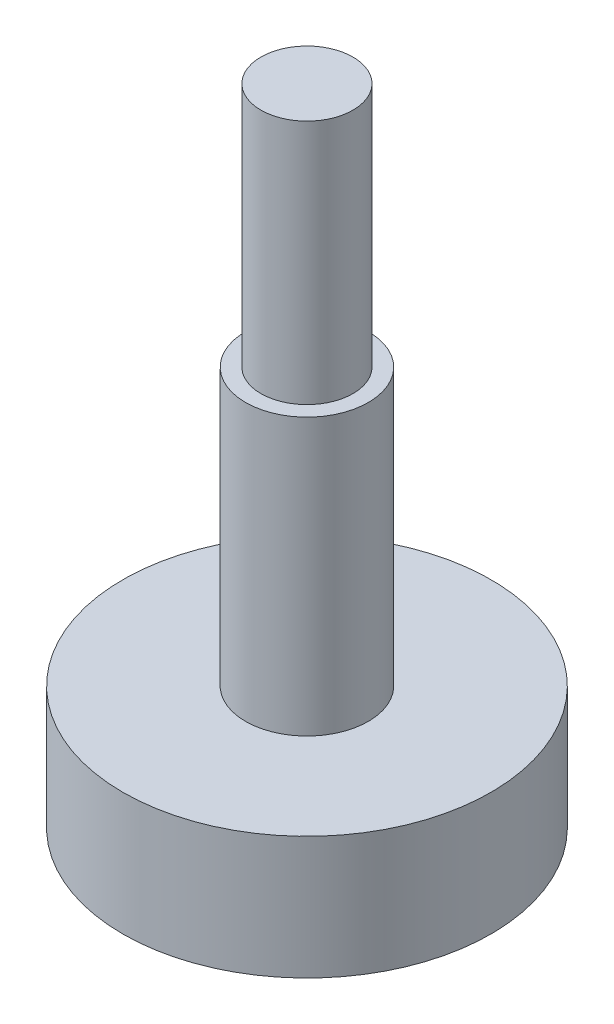
SolidWorks part; units mm, degrees
ref_plane "Front Plane" through (0, 0, 0) normal (0, 0, 1) x (1, 0, 0)
ref_plane "Top Plane" through (0, 0, 0) normal (0, 1, 0) x (1, 0, 0)
ref_plane "Right Plane" through (0, 0, 0) normal (1, 0, 0) x (0, 0, -1)
sketch "Sketch1" plane through (0, 0, 0) normal (0, 0, 1) x (1, 0, 0)
  line L0 (0, 0) -> (6, 0)
  line L1 (5.5, 0) -> (-5.5, 0) construction
  line L2 (6, 0) -> (6, 4)
  line L3 (6, 4) -> (2, 4)
  line L4 (2, 4) -> (2, 13)
  line L5 (2, 13) -> (1.5, 13)
  line L6 (0, -5.5) -> (0, 5.5) construction
  line L7 (0, 21) -> (0, 0)
  line L8 (1.5, 13) -> (1.5, 21)
  line L9 (1.5, 21) -> (0, 21)
  dimension "D1" = 4
  dimension "D2" = 6
  dimension "D3" = 2
  dimension "D4" = 1.5
  dimension "D5" = 17
  dimension "D6" = 8
revolve "Revolve1" add sketch "Sketch1" angle 360 about L7
sketch "Sketch2" plane through (0, 0, 0) normal (0, -1, 0) x (1, 0, 0)
  line L1 (0, -1.7321) -> (1.5, -0.866)
  line L2 (1.5, -0.866) -> (1.5, 0.866)
  line L3 (1.5, 0.866) -> (0, 1.7321)
  line L4 (0, 1.7321) -> (-1.5, 0.866)
  line L5 (-1.5, 0.866) -> (-1.5, -0.866)
  line L6 (-1.5, -0.866) -> (0, -1.7321)
  circle A0 centre (0, 0) radius 1.5 construction
  dimension "D1" = 3
extrude "Cut-Extrude1" cut sketch "Sketch2" against normal blind 2
